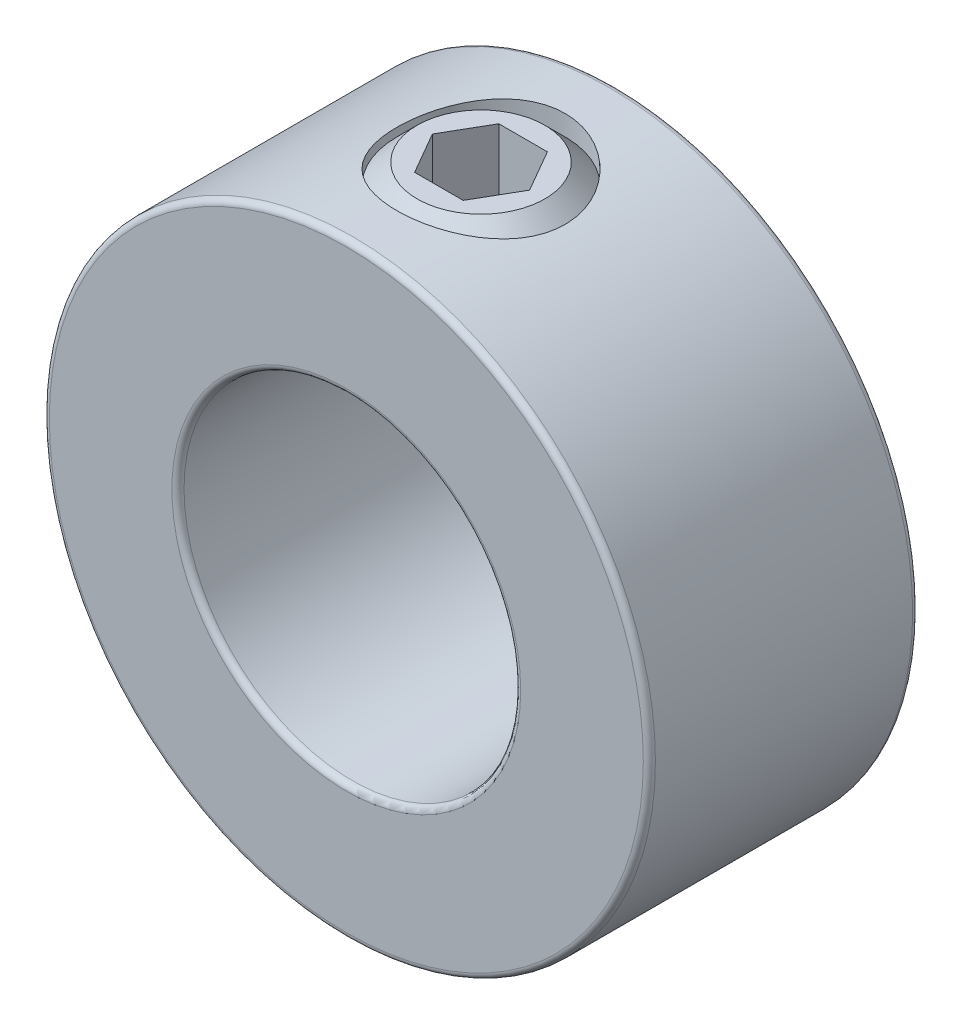
SolidWorks part; units mm, degrees
ref_plane "Front Plane" through (0, 0, 0) normal (0, 0, 1) x (1, 0, 0)
ref_plane "Top Plane" through (0, 0, 0) normal (0, 1, 0) x (1, 0, 0)
ref_plane "Right Plane" through (0, 0, 0) normal (1, 0, 0) x (0, 0, -1)
sketch "Sketch1" plane through (0, 0, 0) normal (0, 0, 1) x (1, 0, 0)
  circle A0 centre (0, 0) radius 14.2875
  circle A1 centre (0, 0) radius 7.9375
  point P4 (14.2875, 0)
  dimension "Bore Dia" = 15.875
  dimension "OD" = 28.575
extrude "Extrude1" add sketch "Sketch1" along normal mid plane 12.7
sketch "Sketch2" plane through (41.275, 0, 0) normal (0, -1, 0) x (0, 0, -1)
  line L0 (6.35, -41.275) -> (-6.35, -41.275) construction
  line L1 (-6.35, -26.9875) -> (-6.35, -55.5625) construction
  line L2 (6.35, -55.5625) -> (6.35, -26.9875) construction
  circle A0 centre (0, -41.275) radius 3.9688
  point P7 (0, -45.2437)
  dimension "Set Screw Dia" = 7.9375
extrude "Cut-Extrude1" cut sketch "Sketch2" against normal through all
fillet "Fillet1" radius 0.2858 4 edges at (7.9375, 0, -6.35) (7.9375, 0, 6.35) (14.2875, 0, -6.35) (14.2875, 0, 6.35)
sketch "Sketch3" plane through (0, 0, 0) normal (0, 0, 1) x (1, 0, 0)
  line L0 (-3.0102, 7.9375) -> (-1.1502, 7.9375)
  line L1 (0, 9.0877) -> (-1.1502, 7.9375)
  line L2 (0, 9.0877) -> (0, 14.2875)
  line L3 (0, 14.2875) -> (-3.0102, 14.2875)
  line L4 (-3.9688, 8.896) -> (-3.9688, 13.329)
  line L5 (0, 7.9375) -> (0, 0) construction
  line L6 (-3.9688, 8.896) -> (-3.9688, 7.9375) construction
  line L7 (-3.9688, 7.9375) -> (-3.0102, 7.9375) construction
  line L8 (-3.9688, 13.329) -> (-3.9688, 14.2875) construction
  line L9 (-3.0102, 7.9375) -> (-3.9688, 8.896)
  line L10 (-3.9688, 13.329) -> (-3.0102, 14.2875)
  line L11 (-3.9688, 14.2875) -> (-3.0102, 14.2875) construction
  line L12 (-1.1502, 7.9375) -> (0, 7.9375) construction
  line L13 (0, 7.9375) -> (0, 9.0877) construction
  circle A1 centre (0, 0) radius 7.9375 construction
  dimension "D1" = 1.1502
  dimension "D2" = 0.9585
  dimension "Screw Length" = 6.35
revolve "Revolve1" add sketch "Sketch3" angle 360 about L5
sketch "Sketch4" plane through (3.3734, 14.2875, 0) normal (0, -1, 0) x (0, 0, -1)
  line L1 (0, -1.0821) -> (-1.9844, -2.2278)
  line L2 (-1.9844, -2.2278) -> (-1.9844, -4.5191)
  line L3 (-1.9844, -4.5191) -> (0, -5.6648)
  line L4 (0, -5.6648) -> (1.9844, -4.5191)
  line L5 (1.9844, -4.5191) -> (1.9844, -2.2278)
  line L6 (1.9844, -2.2278) -> (0, -1.0821)
  circle A0 centre (0, -3.3734) radius 1.9844 construction
  circle A1 centre (0, -3.3734) radius 2.2914 construction
  dimension "D1" = 4.5827
  dimension "Hex Size" = 3.9688
extrude "Cut-Extrude2" cut sketch "Sketch4" along normal blind 3.9688
equation "\"D1@Fillet1\" = \"OD@Sketch1\"*.01"
equation "\"D1@Cut-Extrude2\" = \"Hex Size@Sketch4\""
equation "\"D2@Sketch3\" =(\"Set Screw Dia@Sketch2\"-\"D1@Sketch4\")/3.5"
equation "\"D1@Sketch3\" = \"D2@Sketch3\"*1.2"
